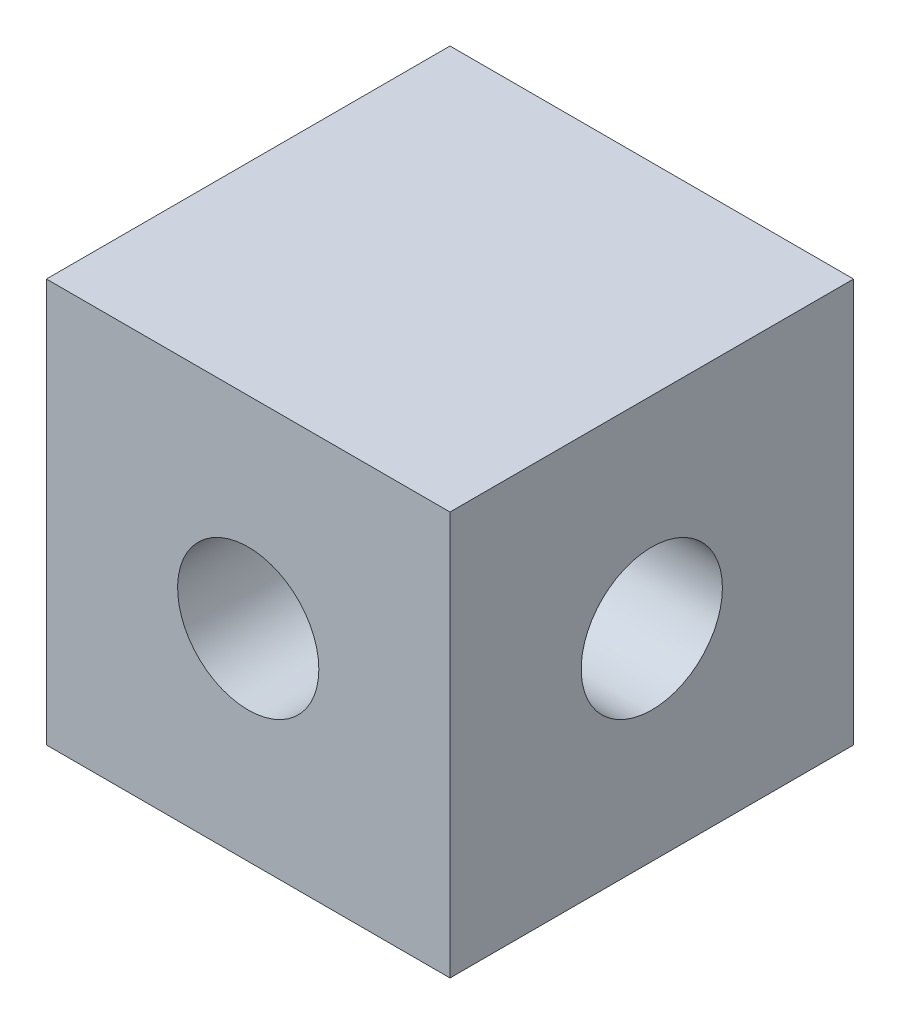
SolidWorks part; units mm, degrees
ref_plane "Front Plane" through (0, 0, 0) normal (0, 0, 1) x (1, 0, 0)
ref_plane "Top Plane" through (0, 0, 0) normal (0, 1, 0) x (1, 0, 0)
ref_plane "Right Plane" through (0, 0, 0) normal (1, 0, 0) x (0, 0, -1)
sketch "Sketch1" plane through (0, 0, 0) normal (0, 0, 1) x (1, 0, 0)
  line L1 (5, -5) -> (-5, -5)
  line L2 (5, -5) -> (5, 5)
  line L3 (5, 5) -> (-5, 5)
  line L4 (-5, -5) -> (-5, 5)
  line L5 (5, -5) -> (-5, 5) construction
  line L6 (5, 5) -> (-5, -5) construction
  circle A0 centre (0, 0) radius 1.75
  point P0 (0, 0)
  dimension "D3" = 3.5
  dimension "D1" = 10
  dimension "D2" = 10
extrude "Boss-Extrude1" add sketch "Sketch1" along normal blind 10
sketch "Sketch2" plane through (5, 0, 0) normal (1, 0, 0) x (0, 0, -1)
  line L0 (-10, -5) -> (0, -5) construction
  circle A0 centre (-5, 0) radius 1.75
  point P5 (-5, -5)
  dimension "D1" = 3.5
extrude "Cut-Extrude1" cut sketch "Sketch2" against normal blind 8 contours A0
